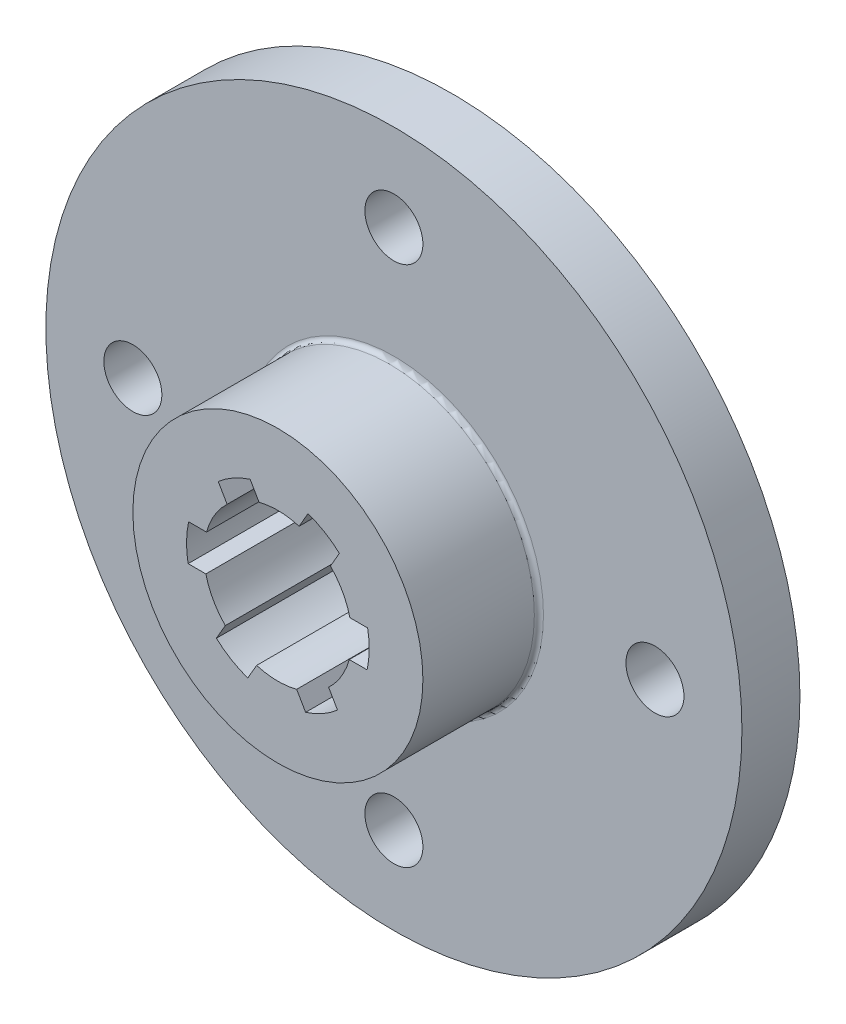
SolidWorks part; units mm, degrees
ref_plane "Front Plane" through (0, 0, 0) normal (0, 0, 1) x (1, 0, 0)
ref_plane "Top Plane" through (0, 0, 0) normal (0, 1, 0) x (1, 0, 0)
ref_plane "Right Plane" through (0, 0, 0) normal (1, 0, 0) x (0, 0, -1)
sketch "Sketch1" plane through (0, 0, 0) normal (0, 1, 0) x (1, 0, 0)
  line L0 (38.1, 3.175) -> (0, 3.175)
  line L1 (0, 3.175) -> (0, -3.175)
  line L2 (0, -3.175) -> (38.1, -3.175)
  line L3 (38.1, -3.175) -> (38.1, 3.175)
  line L4 (0, 3.175) -> (0, -3.175) construction
revolve "Revolve1" add sketch "Sketch1" angle 360 about L4
sketch "Sketch2" plane through (0, 0, 3.175) normal (0, 0, 1) x (1, 0, 0)
  circle A0 centre (0, 0) radius 15.875
extrude "Boss-Extrude1" add sketch "Sketch2" along normal blind 12.7
sketch "Sketch3" plane through (0, 0, 15.875) normal (0, 0, 1) x (1, 0, 0)
  line L0 (-7.8136, 2.1348) -> (-9.7695, 2.1348)
  line L1 (-9.8245, -1.8652) -> (-7.8823, -1.8652)
  line L2 (-5.7556, -5.6994) -> (-6.7336, -7.3932)
  line L3 (-3.297, -9.4409) -> (-2.3259, -7.7589)
  line L4 (2.058, -7.8342) -> (3.0359, -9.528)
  line L5 (6.5275, -7.5757) -> (5.5564, -5.8937)
  line L6 (7.8136, -2.1348) -> (9.7695, -2.1348)
  line L7 (9.8245, 1.8652) -> (7.8823, 1.8652)
  line L8 (5.7556, 5.6994) -> (6.7336, 7.3932)
  line L9 (3.297, 9.4409) -> (2.3259, 7.7589)
  line L10 (-2.058, 7.8342) -> (-3.0359, 9.528)
  line L11 (-6.5275, 7.5757) -> (-5.5564, 5.8937)
  arc A0 (-5.5564, 5.8937) -> (-7.8136, 2.1348) centre (0, 0) ccw
  arc A1 (-9.7695, 2.1348) -> (-9.8245, -1.8652) centre (0, 0) ccw
  arc A2 (-7.8823, -1.8652) -> (-5.7556, -5.6994) centre (0, 0) ccw
  arc A3 (-6.7336, -7.3932) -> (-3.297, -9.4409) centre (0, 0) ccw
  arc A4 (-2.3259, -7.7589) -> (2.058, -7.8342) centre (0, 0) ccw
  arc A5 (3.0359, -9.528) -> (6.5275, -7.5757) centre (0, 0) ccw
  arc A6 (5.5564, -5.8937) -> (7.8136, -2.1348) centre (0, 0) ccw
  arc A7 (9.7695, -2.1348) -> (9.8245, 1.8652) centre (0, 0) ccw
  arc A8 (7.8823, 1.8652) -> (5.7556, 5.6994) centre (0, 0) ccw
  arc A9 (6.7336, 7.3932) -> (3.297, 9.4409) centre (0, 0) ccw
  arc A10 (2.3259, 7.7589) -> (-2.058, 7.8342) centre (0, 0) ccw
  arc A11 (-3.0359, 9.528) -> (-6.5275, 7.5757) centre (0, 0) ccw
extrude "Cut-Extrude1" cut sketch "Sketch3" against normal blind 14.986
hole_wizard "Hole1" positions "Sketch7" profile "Sketch6" legacy end condition through all
sketch "Sketch7" plane through (0, 0, -3.175) normal (0, 0, -1) x (-1, 0, 0)
  point P0 (0, 28.575)
  point P1 (-28.575, 0)
  point P2 (28.575, 0)
  point P3 (0, -28.575)
sketch "Sketch6" plane through (0, 28.575, -3.175) normal (1, 0, 0) x (0, 1, 0)
  line L0 (0, 0) -> (0, 19.05)
  line L1 (0, 19.05) -> (3.175, 19.05)
  line L2 (3.175, 19.05) -> (3.175, 0)
  line L3 (3.175, 0) -> (0, 0)
  line L4 (0, 110) -> (0, -10) construction
  dimension "Diameter" = 6.35
  dimension "Depth" = 19.05
sketch "Sketch10" plane through (0, 0, 0.889) normal (0, 0, 1) x (1, 0, 0)
  circle A0 centre (0, 0) radius 4
  dimension "D1" = 8
extrude "Cut-Extrude3" cut sketch "Sketch10" against normal blind 10
fillet "Fillet2" radius 0.5 1 edges at (15.875, 0, 3.175)
